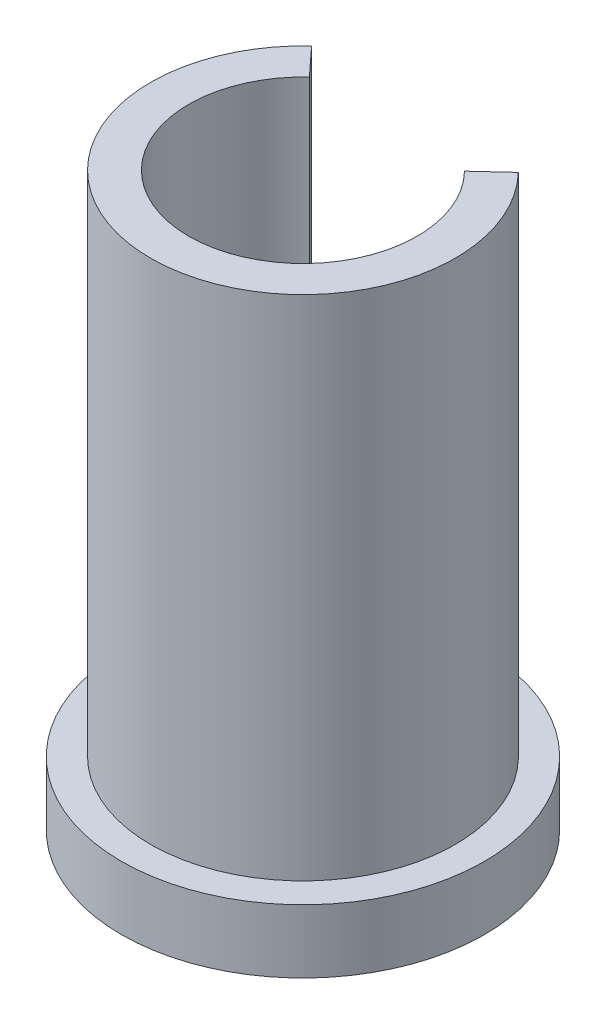
SolidWorks part; units mm, degrees
ref_plane "Front" through (0, 0, 0) normal (0, 0, 1) x (1, 0, 0)
ref_plane "Top" through (0, 0, 0) normal (0, 1, 0) x (1, 0, 0)
ref_plane "Right" through (0, 0, 0) normal (1, 0, 0) x (0, 0, -1)
sketch "Sketch1" plane through (0, 0, 0) normal (0, 1, 0) x (1, 0, 0)
  circle A0 centre (0, 0) radius 14.3
  dimension "D1" = 28.6
extrude "Boss-Extrude1" add sketch "Sketch1" along normal blind 5
sketch "Sketch2" plane through (0, 0, 0) normal (0, -1, 0) x (1, 0, 0)
  circle A0 centre (0, 0) radius 12
  dimension "D1" = 24
extrude "Boss-Extrude2" add sketch "Sketch2" against normal blind 45
sketch "Sketch3" plane through (0, 45, 0) normal (0, 1, 0) x (1, 0, 0)
  circle A0 centre (0, 0) radius 9
  dimension "D1" = 18
extrude "Cut-Extrude1" cut sketch "Sketch3" against normal through all
sketch "Sketch4" plane through (0, 45, 0) normal (0, 1, 0) x (1, 0, 0)
  line L0 (-8.8424, 9.5781) -> (-2.3402, 2.5349)
  line L2 (2.3402, 2.5349) -> (9.3894, 9.0426)
  arc A0 (2.3402, 2.5349) -> (-2.3402, 2.5349) centre (0, 0) ccw
  arc A1 (9.3894, 9.0426) -> (-8.8424, 9.5781) centre (0, 0) ccw
  dimension "D1" = 3.45
extrude "Cut-Extrude3" cut sketch "Sketch4" against normal blind 40
